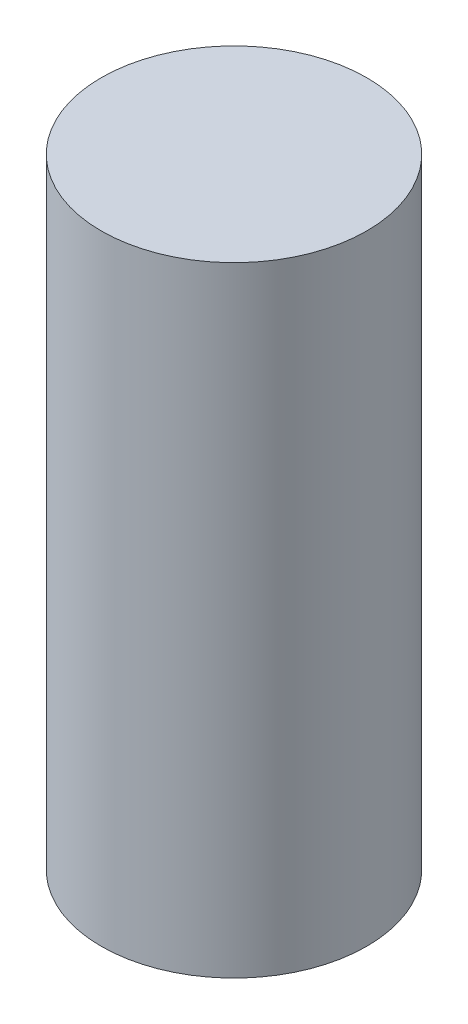
SolidWorks part; units mm, degrees
ref_plane "前视基准面" through (0, 0, 0) normal (0, 0, 1) x (1, 0, 0)
ref_plane "上视基准面" through (0, 0, 0) normal (0, 1, 0) x (1, 0, 0)
ref_plane "右视基准面" through (0, 0, 0) normal (1, 0, 0) x (0, 0, -1)
sketch "草图1" plane through (0, 0, 0) normal (0, 1, 0) x (1, 0, 0)
  circle A0 centre (0, 0) radius 6
extrude "凸台-拉伸1" add sketch "草图1" along normal blind 28 contours A0
